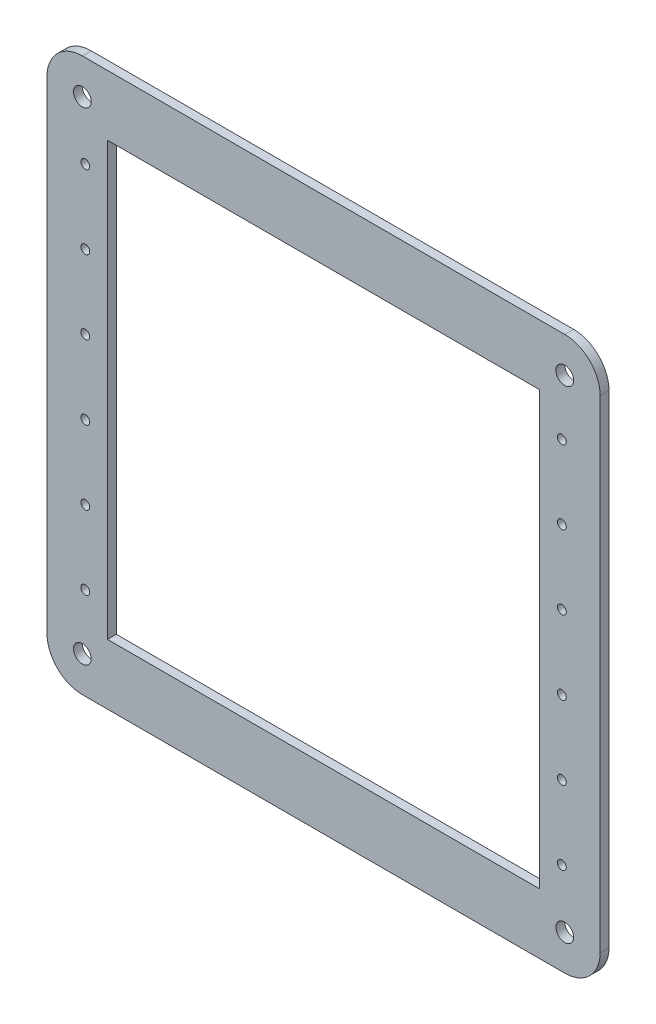
SolidWorks part; units mm, degrees
material "Plain Carbon Steel"
ref_plane "Front Plane" through (0, 0, 0) normal (0, 0, 1) x (1, 0, 0)
ref_plane "Top Plane" through (0, 0, 0) normal (0, 1, 0) x (1, 0, 0)
ref_plane "Right Plane" through (0, 0, 0) normal (1, 0, 0) x (0, 0, -1)
sketch "Sketch1" plane through (0, 0, 0) normal (0, 0, 1) x (1, 0, 0)
  line L0 (-97.6863, 97.6863) -> (97.6863, 97.6863)
  line L1 (-109, 125) -> (109, 125)
  line L2 (-125, 109) -> (-125, -109)
  line L3 (-109, -125) -> (109, -125)
  line L4 (125, 109) -> (125, -109)
  line L5 (-125, 125) -> (125, -125) construction
  line L6 (-125, -125) -> (125, 125) construction
  line L7 (97.6863, 97.6863) -> (97.6863, -97.6863)
  line L8 (97.6863, -97.6863) -> (-97.6863, -97.6863)
  line L9 (-97.6863, -97.6863) -> (-97.6863, 97.6863)
  arc A0 (-125, -109) -> (-109, -125) centre (-109, -109) ccw
  arc A1 (109, -125) -> (125, -109) centre (109, -109) ccw
  arc A2 (109, 125) -> (125, 109) centre (109, 109) cw
  arc A3 (-109, 125) -> (-125, 109) centre (-109, 109) ccw
  circle A4 centre (-109, 109) radius 16 construction
  circle A5 centre (-109, 109) radius 4
  circle A6 centre (109, 109) radius 4
  circle A7 centre (109, -109) radius 4
  circle A8 centre (-109, -109) radius 4
  point P0 (0, 0)
  point P19 (-97.6863, 97.6863)
  dimension "D3" = 16
  dimension "D4" = 8
  dimension "D5" = 8
  dimension "D6" = 8
  dimension "D7" = 8
  dimension "D1" = 250
  dimension "D2" = 250
extrude "Boss-Extrude1" add sketch "Sketch1" along normal blind 4
sketch "Sketch2" plane through (0, 0, 4) normal (0, 0, 1) x (1, 0, 0)
  circle A0 centre (-107.6863, 83.3) radius 2
  circle A1 centre (-107.6863, 50) radius 2
  circle A2 centre (-107.6863, 16.7) radius 2
  circle A3 centre (-107.6863, -16.7) radius 2
  circle A4 centre (-107.6863, -50) radius 2
  circle A5 centre (-107.6863, -83.3) radius 2
  circle A6 centre (107.6863, -83.3) radius 2
  circle A7 centre (107.6863, -50) radius 2
  circle A8 centre (107.6863, -16.7) radius 2
  circle A9 centre (107.6863, 16.7) radius 2
  circle A10 centre (107.6863, 50) radius 2
  circle A11 centre (107.6863, 83.3) radius 2
extrude "Cut-Extrude1" cut sketch "Sketch2" against normal blind 10
